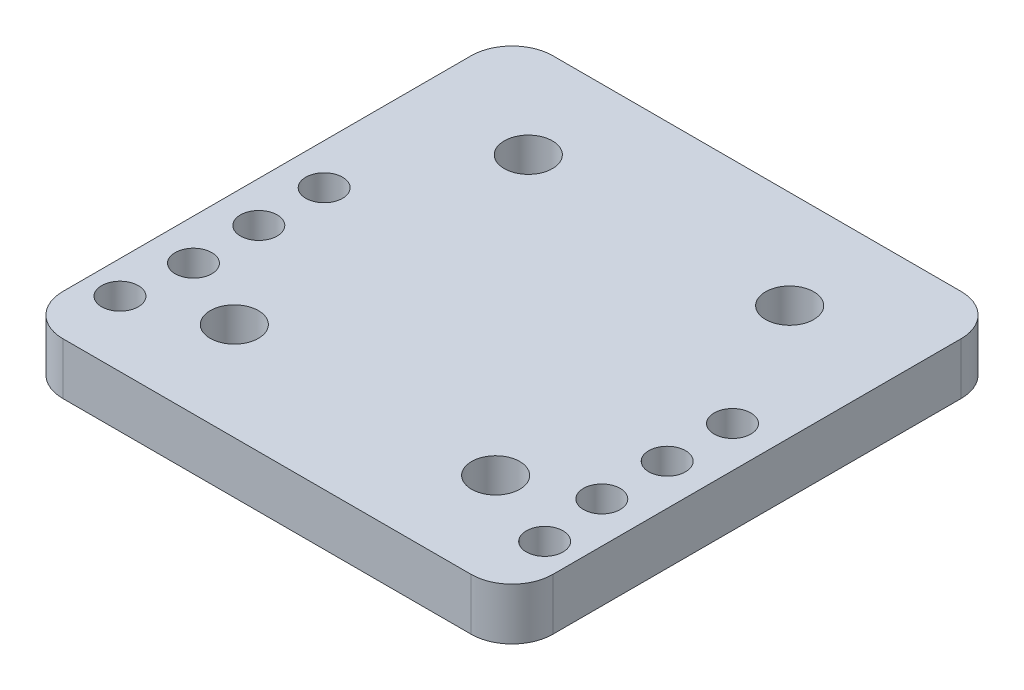
SolidWorks part; units mm, degrees
ref_plane "Front Plane" through (0, 0, 0) normal (0, 0, 1) x (1, 0, 0)
ref_plane "Top Plane" through (0, 0, 0) normal (0, 1, 0) x (1, 0, 0)
ref_plane "Right Plane" through (0, 0, 0) normal (1, 0, 0) x (0, 0, -1)
sketch "Sketch1" plane through (0, 0, 0) normal (0, 1, 0) x (1, 0, 0)
  line L0 (0, 30) -> (60, 30) construction
  line L1 (0, 0) -> (60, 0)
  line L2 (0, 0) -> (0, 60)
  line L3 (0, 60) -> (60, 60)
  line L4 (60, 0) -> (60, 60)
  line L5 (14, 12) -> (46, 12) construction
  line L6 (14, 12) -> (14, 48) construction
  line L7 (14, 48) -> (46, 48) construction
  line L8 (46, 12) -> (46, 48) construction
  line L9 (30, 60) -> (30, 0) construction
  circle A0 centre (14, 48) radius 2.95
  circle A1 centre (46, 48) radius 2.95
  circle A2 centre (46, 12) radius 2.95
  circle A3 centre (14, 12) radius 2.95
  circle A4 centre (56, 8) radius 2.25
  circle A5 centre (4, 8) radius 2.25
  circle A6 centre (55, 16) radius 2.25
  circle A7 centre (55, 24) radius 2.25
  circle A8 centre (55, 32) radius 2.25
  circle A9 centre (5, 32) radius 2.25
  circle A10 centre (5, 24) radius 2.25
  circle A11 centre (5, 16) radius 2.25
  dimension "D1" = 5.9
  dimension "D6" = 4.5
  dimension "D2" = 60
  dimension "D3" = 60
  dimension "D4" = 32
  dimension "D5" = 36
  dimension "D7" = 4
  dimension "D8" = 8
  dimension "D9" = 5
  dimension "D10" = 16
  dimension "D12" = 8
  dimension "D11" = 3
extrude "Boss-Extrude1" add sketch "Sketch1" along normal blind 6.35
fillet "Fillet1" radius 5 4 edges at (0, 3.175, -60) (60, 3.175, 0) (0, 3.175, 0) (60, 3.175, -60)
